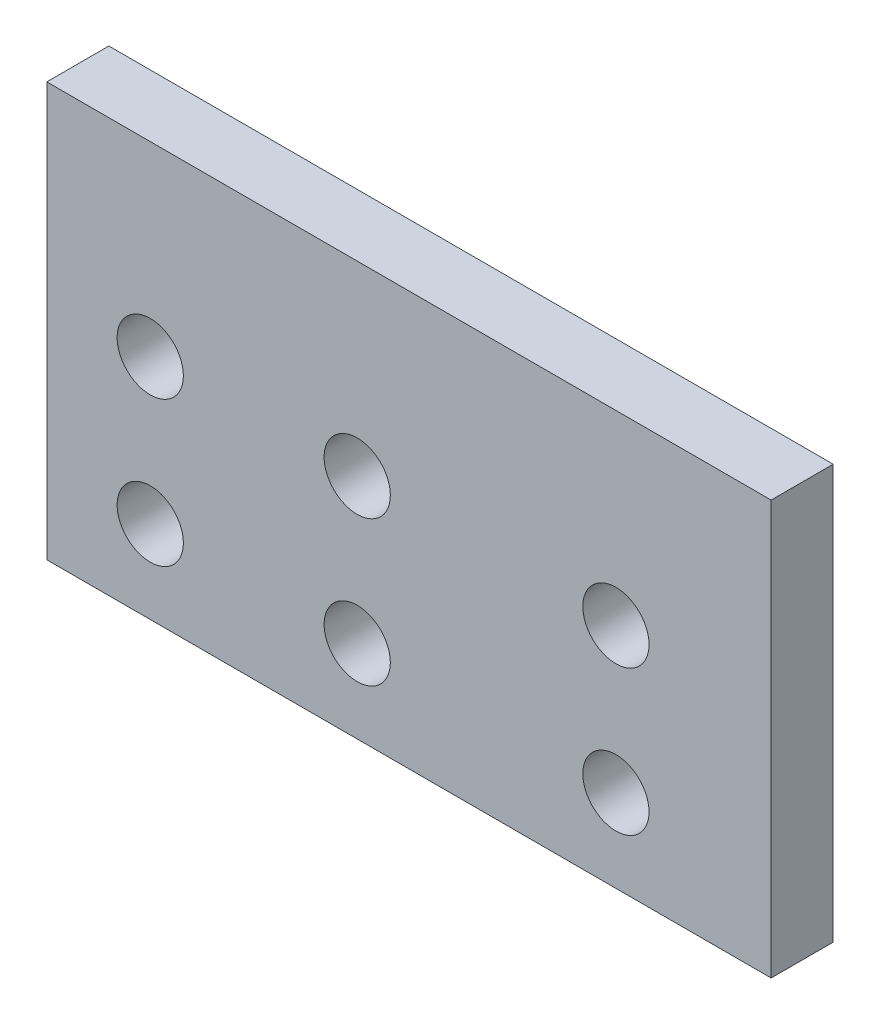
SolidWorks part; units mm, degrees
ref_plane "前视基准面" through (0, 0, 0) normal (0, 0, 1) x (1, 0, 0)
ref_plane "上视基准面" through (0, 0, 0) normal (0, 1, 0) x (1, 0, 0)
ref_plane "右视基准面" through (0, 0, 0) normal (1, 0, 0) x (0, 0, -1)
other "Configuration Table"
sketch "草图1" plane through (0, 0, 0) normal (0, 0, 1) x (1, 0, 0)
  line L0 (-12.5, 1) -> (-12.5, -6) construction
  line L1 (17.5, -10) -> (-17.5, -10)
  line L2 (17.5, -10) -> (17.5, 10)
  line L3 (17.5, 10) -> (-17.5, 10)
  line L4 (-17.5, -10) -> (-17.5, 10)
  line L5 (17.5, -10) -> (-17.5, 10) construction
  line L6 (17.5, 10) -> (-17.5, -10) construction
  circle A0 centre (-12.5, 1) radius 1.6
  circle A2 centre (-12.5, -6) radius 1.6
  circle A4 centre (-2.5, 1) radius 1.6
  circle A5 centre (-2.5, -6) radius 1.6
  circle A6 centre (10, 1) radius 1.6
  circle A7 centre (10, -6) radius 1.6
  point P0 (0, 0)
  dimension "D3" = 3.2
  dimension "D1" = 20
  dimension "D2" = 35
  dimension "D4" = 9
  dimension "D5" = 7
  dimension "D6" = 5
  dimension "D7" = 2
  dimension "D8" = 2
extrude "凸台-拉伸1" add sketch "草图1" along normal blind 3
